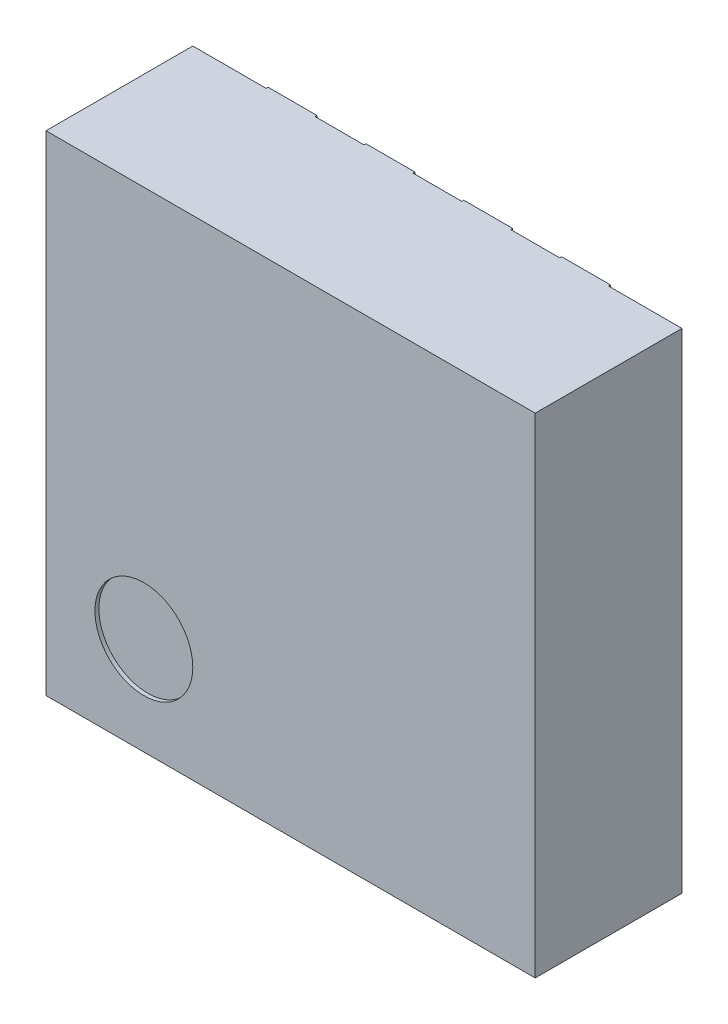
SolidWorks part; units mm, degrees
ref_plane "Front Plane" through (0, 0, 0) normal (0, 0, 1) x (1, 0, 0)
ref_plane "Top Plane" through (0, 0, 0) normal (0, 1, 0) x (1, 0, 0)
ref_plane "Right Plane" through (0, 0, 0) normal (1, 0, 0) x (0, 0, -1)
sketch "Sketch1" plane through (0, 0, 0) normal (0, 0, 1) x (1, 0, 0)
  line L1 (-1.25, 1.25) -> (1.25, 1.25)
  line L2 (-1.25, 1.25) -> (-1.25, -1.25)
  line L3 (-1.25, -1.25) -> (1.25, -1.25)
  line L4 (1.25, 1.25) -> (1.25, -1.25)
  line L5 (-1.25, 1.25) -> (1.25, -1.25) construction
  line L6 (-1.25, -1.25) -> (1.25, 1.25) construction
  point P0 (0, 0)
  dimension "D1" = 2.5
extrude "Boss-Extrude1" add sketch "Sketch1" along normal blind 0.75
sketch "Sketch2" plane through (0, 0, 0.75) normal (0, 0, 1) x (1, 0, 0)
  line L0 (-1.25, 1.25) -> (-1.25, -1.25) construction
  line L1 (-1.25, -1.25) -> (1.25, -1.25) construction
  circle A0 centre (-0.75, -0.75) radius 0.25
  dimension "D1" = 0.5
  dimension "D2" = 0.5
  dimension "D3" = 0.5
extrude "Cut-Extrude1" cut sketch "Sketch2" against normal blind 0.02
sketch "Sketch3" plane through (0, 0, 0) normal (0, 0, -1) x (-1, 0, 0)
  line L0 (1.25, -1.25) -> (-1.25, -1.25) construction
  line L1 (0.625, -1.25) -> (0.875, -1.25)
  line L2 (0.625, -1.25) -> (0.625, -0.75)
  line L3 (0.625, -0.75) -> (0.875, -0.75)
  line L4 (0.875, -1.25) -> (0.875, -0.75)
  line L5 (0, 0) -> (0, -1.25) construction
  line L6 (0.125, -1.25) -> (0.125, -0.75)
  line L7 (0.125, -0.75) -> (0.375, -0.75)
  line L8 (0.375, -1.25) -> (0.375, -0.75)
  line L9 (0.125, -1.25) -> (0.375, -1.25)
  line L10 (-0.375, -1.25) -> (-0.375, -0.75)
  line L11 (-0.375, -0.75) -> (-0.125, -0.75)
  line L12 (-0.125, -1.25) -> (-0.125, -0.75)
  line L13 (-0.375, -1.25) -> (-0.125, -1.25)
  line L14 (-0.875, -1.25) -> (-0.875, -0.75)
  line L15 (-0.875, -0.75) -> (-0.625, -0.75)
  line L16 (-0.625, -1.25) -> (-0.625, -0.75)
  line L17 (-0.875, -1.25) -> (-0.625, -1.25)
  line L18 (0, 0) -> (1.25, 0) construction
  line L19 (1.25, 1.25) -> (1.25, -1.25) construction
  line L20 (-0.875, 1.25) -> (-0.625, 1.25)
  line L21 (-0.625, 1.25) -> (-0.625, 0.75)
  line L22 (-0.875, 0.75) -> (-0.625, 0.75)
  line L23 (-0.875, 1.25) -> (-0.875, 0.75)
  line L24 (-0.375, 1.25) -> (-0.125, 1.25)
  line L25 (-0.125, 1.25) -> (-0.125, 0.75)
  line L26 (-0.375, 0.75) -> (-0.125, 0.75)
  line L27 (-0.375, 1.25) -> (-0.375, 0.75)
  line L28 (0.125, 1.25) -> (0.375, 1.25)
  line L29 (0.375, 1.25) -> (0.375, 0.75)
  line L30 (0.125, 0.75) -> (0.375, 0.75)
  line L31 (0.125, 1.25) -> (0.125, 0.75)
  line L32 (0.875, 1.25) -> (0.875, 0.75)
  line L33 (0.625, 0.75) -> (0.875, 0.75)
  line L34 (0.625, 1.25) -> (0.625, 0.75)
  line L35 (0.625, 1.25) -> (0.875, 1.25)
  line L37 (-0.75, 0.14) -> (0.75, 0.14)
  line L38 (-0.75, 0.14) -> (-0.75, -0.14)
  line L39 (-0.75, -0.14) -> (0.75, -0.14)
  line L40 (0.75, 0.14) -> (0.75, -0.14)
  line L41 (-0.75, 0.14) -> (0.75, -0.14) construction
  line L42 (-0.75, -0.14) -> (0.75, 0.14) construction
  point P9 (0.75, -1.25)
  point P23 (0.25, -1.25)
  dimension "D1" = 0.25
  dimension "D2" = 0.75
  dimension "D3" = 0.5
  dimension "D5" = 0.5
  dimension "D6" = 0.28
  dimension "D7" = 1.5
  dimension "D4" = 4
extrude "Boss-Extrude2" add sketch "Sketch3" along normal blind 0.01
